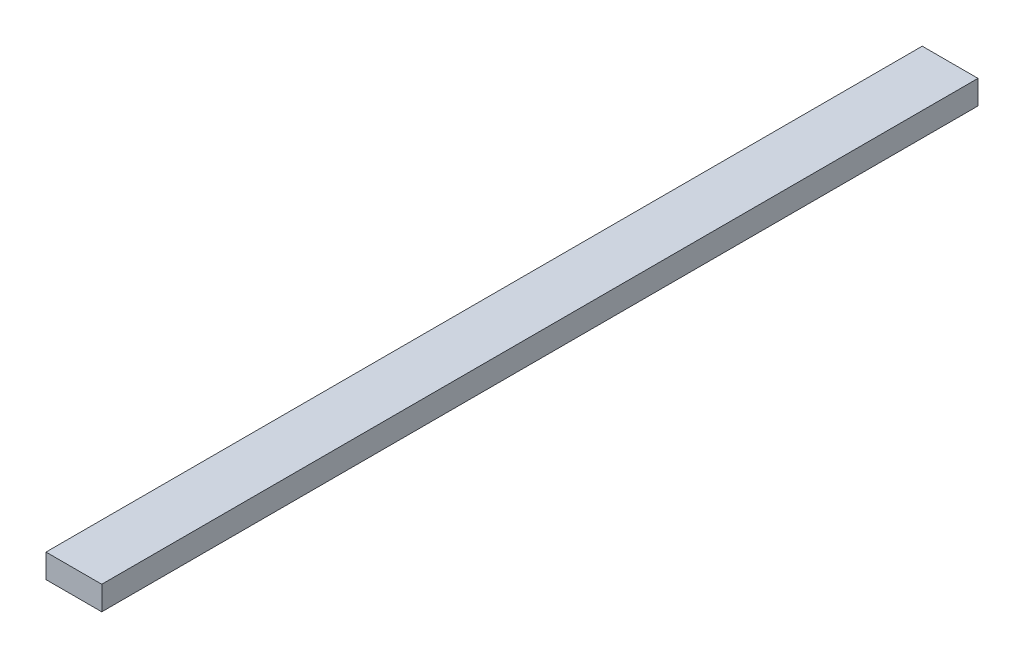
SolidWorks part; units mm, degrees
ref_plane "Front Plane" through (0, 0, 0) normal (0, 0, 1) x (1, 0, 0)
ref_plane "Top Plane" through (0, 0, 0) normal (0, 1, 0) x (1, 0, 0)
ref_plane "Right Plane" through (0, 0, 0) normal (1, 0, 0) x (0, 0, -1)
sketch "Sketch1" plane through (0, 0, 0) normal (0, 0, 1) x (1, 0, 0)
  line L1 (44.45, 19.05) -> (-44.45, 19.05)
  line L2 (44.45, 19.05) -> (44.45, -19.05)
  line L3 (44.45, -19.05) -> (-44.45, -19.05)
  line L4 (-44.45, 19.05) -> (-44.45, -19.05)
  line L5 (44.45, 19.05) -> (-44.45, -19.05) construction
  line L6 (44.45, -19.05) -> (-44.45, 19.05) construction
  point P0 (0, 0)
  dimension "D1" = 88.9
  dimension "D2" = 38.1
extrude "Boss-Extrude1" add sketch "Sketch1" along normal mid plane 1397
